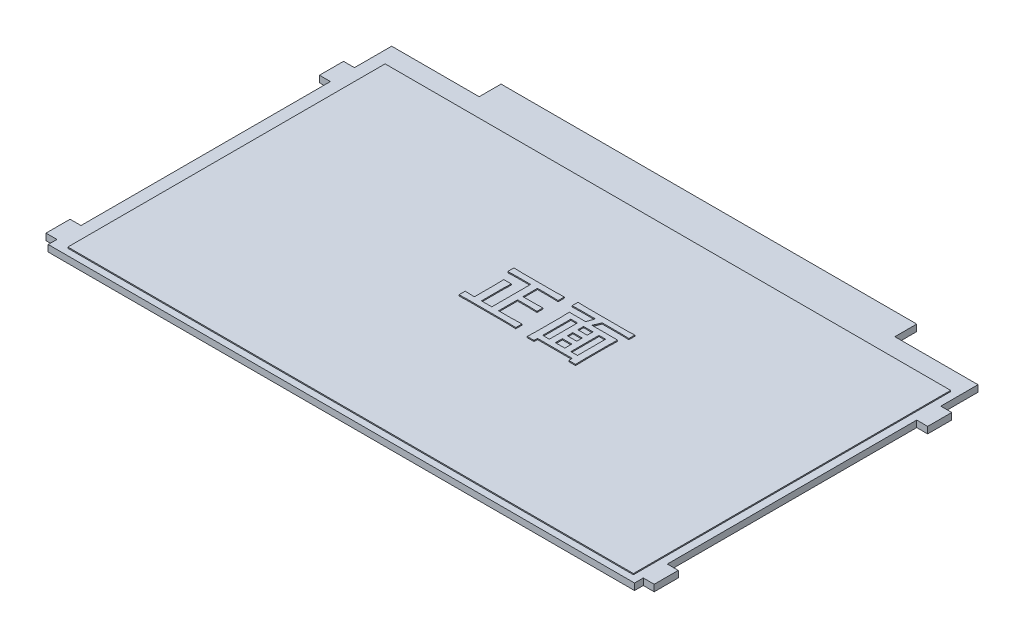
SolidWorks part; units mm, degrees
ref_plane "Front" through (0, 0, 0) normal (0, 0, 1) x (1, 0, 0)
ref_plane "Top" through (0, 0, 0) normal (0, 1, 0) x (1, 0, 0)
ref_plane "Right" through (0, 0, 0) normal (1, 0, 0) x (0, 0, -1)
sketch "Sketch1" plane through (0, 0, 0) normal (0, 1, 0) x (1, 0, 0)
  line L1 (0, 0) -> (268, 0)
  line L2 (0, 0) -> (0, -157)
  line L3 (0, -157) -> (268, -157)
  line L4 (268, 0) -> (268, -157)
  line L5 (40, 0) -> (230, 0)
  line L6 (40, 0) -> (40, 10)
  line L7 (40, 10) -> (230, 10)
  line L8 (230, 0) -> (230, 10)
  line L9 (268, -28) -> (273, -28)
  line L10 (268, -28) -> (268, -17)
  line L11 (268, -17) -> (273, -17)
  line L12 (273, -28) -> (273, -17)
  line L13 (268, -153) -> (273, -153)
  line L14 (268, -153) -> (268, -142)
  line L15 (268, -142) -> (273, -142)
  line L16 (273, -153) -> (273, -142)
  line L17 (0, -153) -> (-5, -153)
  line L18 (0, -153) -> (0, -142)
  line L19 (0, -142) -> (-5, -142)
  line L20 (-5, -153) -> (-5, -142)
  line L21 (0, -28) -> (-5, -28)
  line L22 (0, -28) -> (0, -17)
  line L23 (0, -17) -> (-5, -17)
  line L24 (-5, -28) -> (-5, -17)
  dimension "D1" = 268
  dimension "D2" = 157
  dimension "D3" = 190
  dimension "D4" = 40
  dimension "D5" = 5
  dimension "D6" = 11
  dimension "D7" = 5
  dimension "D8" = 11
  dimension "D9" = 4
  dimension "D10" = 17
  dimension "D11" = 5
  dimension "D12" = 11
  dimension "D13" = 5
  dimension "D14" = 11
  dimension "D15" = 4
  dimension "D16" = 17
  dimension "D17" = 10
extrude "Boss-Extrude1" add sketch "Sketch1" along normal blind 3 contours L4 L1 L2 L3 | L1 L8 L7 L6 | L20 L17 L2 L19 | L24 L21 L2 L23 | L13 L16 L15 L4 | L9 L12 L11 L4
sketch "Sketch2" plane through (0, 3, 0) normal (0, 1, 0) x (1, 0, 0)
  text T0 "正面" font "黑体" height 20
extrude "Boss-Extrude2" add sketch "Sketch2" along normal blind 1
sketch "Sketch3" plane through (0, 0, 0) normal (0, -1, 0) x (-1, 0, 0)
  line L0 (-40, 10) -> (-230, 10) construction
  line L1 (-183, 10) -> (-160, 10)
  line L2 (-183, 10) -> (-183, 0)
  line L3 (-183, 0) -> (-160, 0)
  line L4 (-160, 10) -> (-160, 0)
  dimension "D1" = 47
  dimension "D2" = 23
  dimension "D3" = 10
extrude "Cut-Extrude1" cut sketch "Sketch3" against normal blind 1
sketch "Sketch4" plane through (0, 3, 0) normal (0, 1, 0) x (1, 0, 0)
  line L0 (0, -28) -> (0, -142) construction
  line L1 (6, -9) -> (264.5, -9)
  line L2 (6, -9) -> (6, -154)
  line L3 (6, -154) -> (264.5, -154)
  line L4 (264.5, -9) -> (264.5, -154)
  line L5 (0, -157) -> (268, -157) construction
  line L6 (268, -28) -> (268, -142) construction
  line L7 (230, 0) -> (268, 0) construction
  dimension "D1" = 6
  dimension "D2" = 3
  dimension "D3" = 3.5
  dimension "D4" = 9
extrude "Boss-Extrude3" add sketch "Sketch4" along normal blind 0.5
